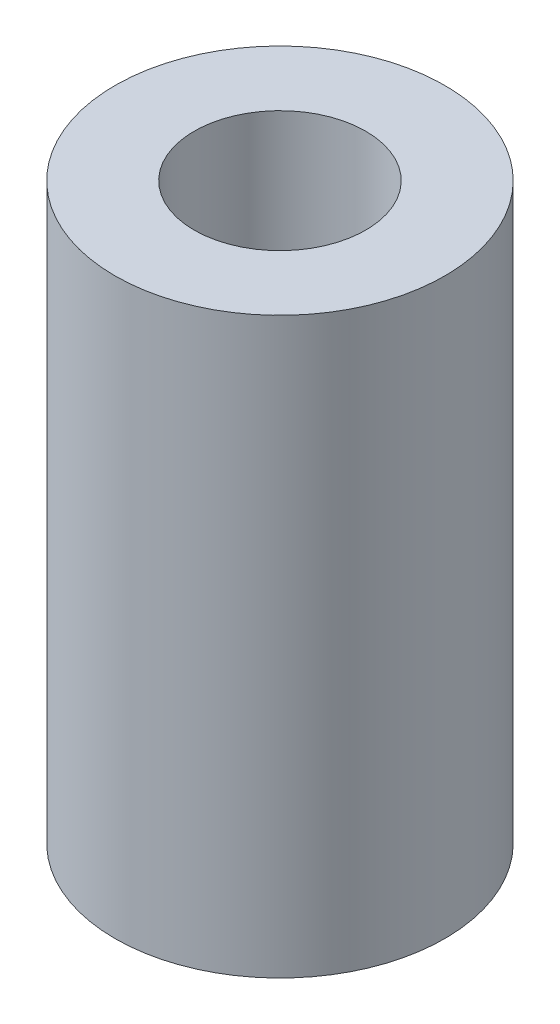
SolidWorks part; units mm, degrees
ref_plane "Front Plane" through (0, 0, 0) normal (0, 0, 1) x (1, 0, 0)
ref_plane "Top Plane" through (0, 0, 0) normal (0, 1, 0) x (1, 0, 0)
ref_plane "Right Plane" through (0, 0, 0) normal (1, 0, 0) x (0, 0, -1)
sketch "Sketch1" plane through (0, 0, 0) normal (0, 1, 0) x (1, 0, 0)
  circle A0 centre (0, 0) radius 3.175
  circle A1 centre (0, 0) radius 1.651
  dimension "D1" = 3.302
  dimension "D2" = 6.35
extrude "Boss-Extrude1" add sketch "Sketch1" along normal blind 11.049
